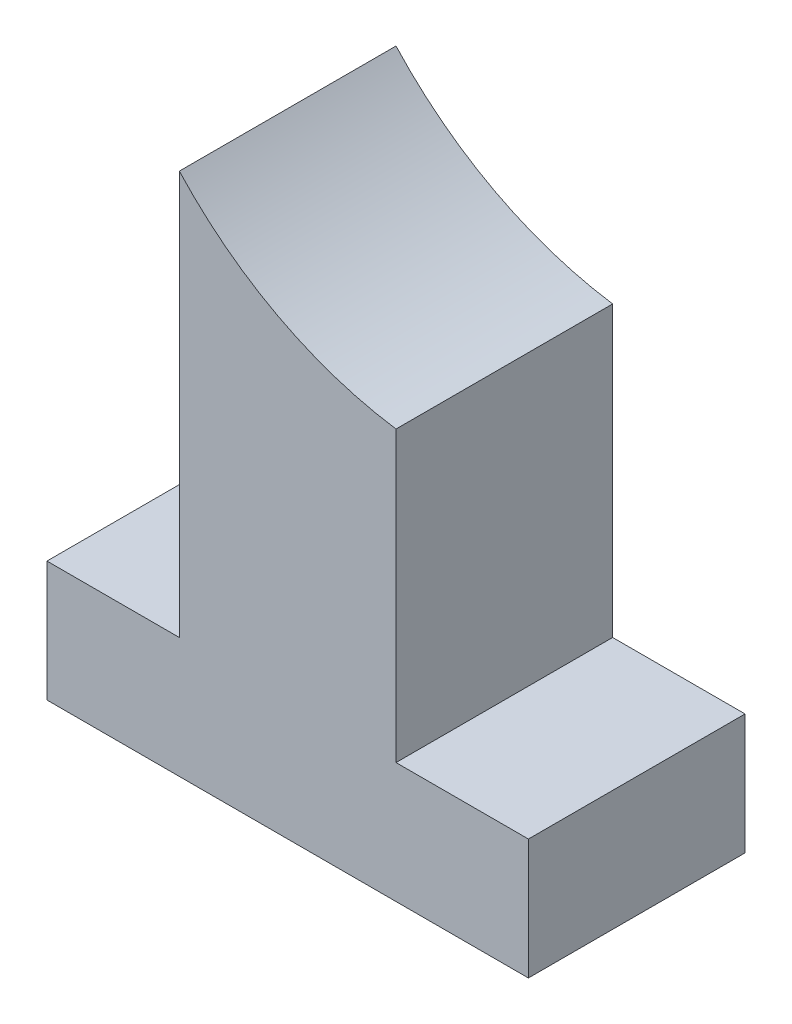
SolidWorks part; units mm, degrees
ref_plane "Front Plane" through (0, 0, 0) normal (0, 0, 1) x (1, 0, 0)
ref_plane "Top Plane" through (0, 0, 0) normal (0, 1, 0) x (1, 0, 0)
ref_plane "Right Plane" through (0, 0, 0) normal (1, 0, 0) x (0, 0, -1)
sketch "Sketch1" plane through (0, 0, 0) normal (0, 0, 1) x (1, 0, 0)
  line L0 (275, 1088.9443) -> (275, 250)
  line L1 (275, 250) -> (0, 250)
  line L2 (0, 250) -> (0, 0)
  line L3 (0, 0) -> (1000, 0)
  line L4 (1000, 0) -> (1000, 250)
  line L5 (1000, 250) -> (725, 250)
  line L6 (725, 250) -> (725, 850)
  arc A0 (275, 1088.9443) -> (725, 850) centre (837.2934, 1604.6915) ccw
  point P3 (0, 0)
  point P10 (0, 0)
  dimension "D2" = 763
  dimension "D1" = 1000
  dimension "D3" = 250
  dimension "D4" = 450
  dimension "D5" = 275
  dimension "D6" = 600
extrude "Boss-Extrude1" add sketch "Sketch1" along normal blind 450
